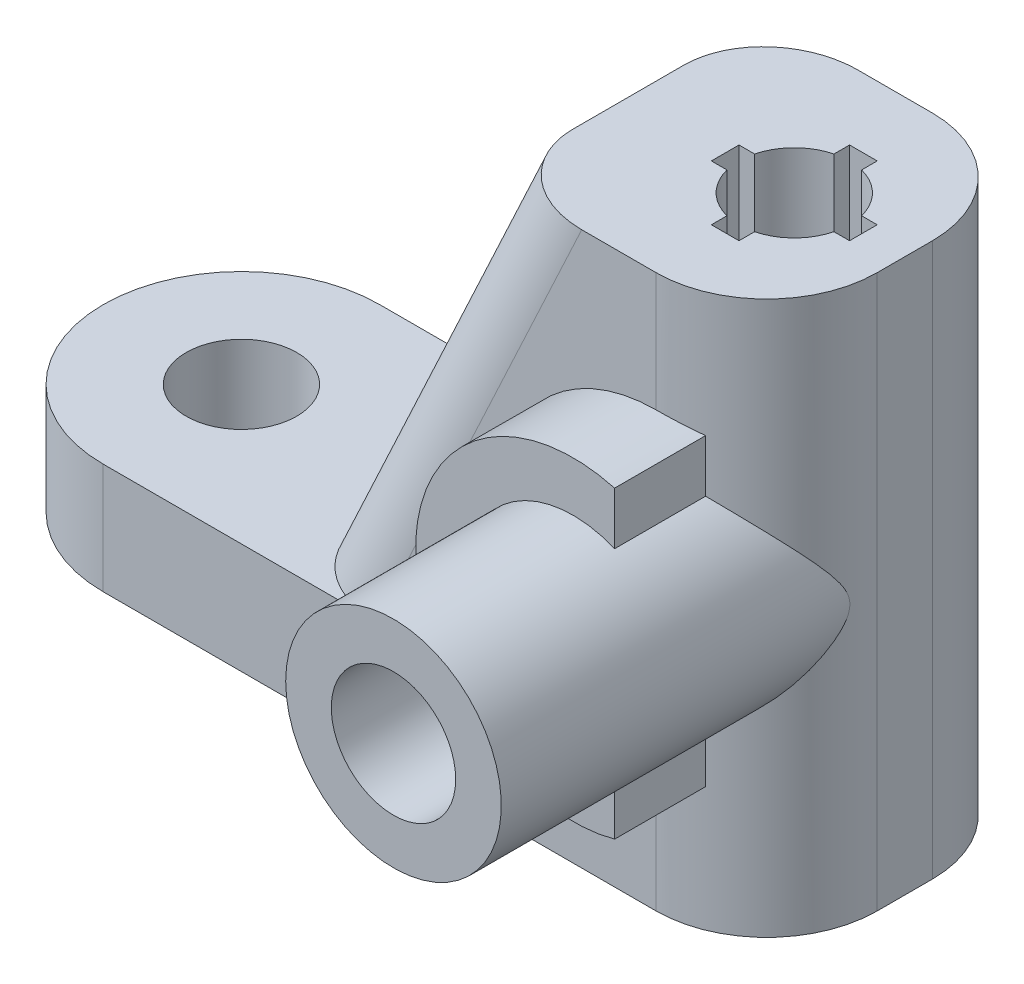
SolidWorks part; units mm, degrees
ref_plane "Front Plane" through (0, 0, 0) normal (0, 0, 1) x (1, 0, 0)
ref_plane "Top Plane" through (0, 0, 0) normal (0, 1, 0) x (1, 0, 0)
ref_plane "Right Plane" through (0, 0, 0) normal (1, 0, 0) x (0, 0, -1)
sketch "Sketch1" plane through (0, 0, 0) normal (0, 0, 1) x (1, 0, 0)
  line L0 (15, 0) -> (-15, 0) construction
  line L1 (-15, 10) -> (15, 10)
  line L2 (-15, 10) -> (-15, -10)
  line L3 (-15, -10) -> (15, -10)
  line L4 (15, 10) -> (15, -10)
  line L5 (-15, 10) -> (15, -10) construction
  line L6 (-15, -10) -> (15, 10) construction
  circle A0 centre (0, 0) radius 4 construction
  circle A1 centre (6, 0) radius 4 construction
  point P0 (0, 0)
  dimension "D3" = 8
  dimension "D4" = 8
  dimension "D5" = 6
  dimension "D1" = 20
  dimension "D2" = 30
extrude "Boss-Extrude1" add sketch "Sketch1" along normal blind 10
sketch "Sketch3" plane through (0, 10, 0) normal (0, 1, 0) x (1, 0, 0)
  line L0 (-15, -5) -> (15, -5) construction
  line L1 (-15, -10) -> (-15, 0) construction
  line L2 (15, -10) -> (15, 0) construction
  circle A0 centre (11, -5) radius 2
  dimension "D1" = 4
  dimension "D2" = 4
extrude "Cut-Extrude1" cut sketch "Sketch3" against normal through all
sketch "Sketch4" plane through (0, -10, 0) normal (0, -1, 0) x (1, 0, 0)
  line L0 (-15, 5) -> (15, 5) construction
  line L1 (-15, 10) -> (-15, 0) construction
  line L2 (15, 10) -> (15, 0) construction
  circle A0 centre (-9, 5) radius 2
  circle A2 centre (11, 5) radius 2 construction
  dimension "D1" = 4
  dimension "D2" = 20
extrude "Cut-Extrude2" cut sketch "Sketch4" against normal through all
fillet "Fillet1" radius 4 2 edges at (15, 0, 10) (15, 0, 0)
sketch "Sketch5" plane through (0, 0, 10) normal (0, 0, 1) x (1, 0, 0)
  line L0 (11, -10) -> (11, 10) construction
  circle A0 centre (11, 0) radius 3.9
  dimension "D1" = 7.8
extrude "Boss-Extrude2" add sketch "Sketch5" along normal offset from surface 0.5 and the other way up to surface other way up to face at (13.4142, 0, 8.4142)
sketch "Sketch6" plane through (0, 0, 10) normal (0, 0, 1) x (1, 0, 0)
  line L0 (-15, -6) -> (-2.4609, -6)
  line L2 (-2.4609, -6) -> (5, 10)
  line L3 (11, 10) -> (-15, 10) construction
  line L4 (5, 10) -> (-15, 10)
  line L5 (-15, 10) -> (-15, -6)
  line L6 (15, 10) -> (15, -10) construction
  line L7 (-15, -10) -> (11, -10) construction
  line L8 (-15, 10) -> (-15, -10) construction
  dimension "D1" = 10
  dimension "D2" = 4
  dimension "D3" = 115
extrude "Cut-Extrude3" cut sketch "Sketch6" against normal through all
fillet "Fillet3" radius 3 2 edges at (1.2695, 2, 10) (1.2695, 2, 0)
sketch "Sketch7" plane through (0, 0, 10) normal (0, 0, 1) x (1, 0, 0)
  line L0 (12.5, 5.4991) -> (12.5, -5.4991)
  line L1 (11, 3.9) -> (11, 10) construction
  arc A0 (12.5, 5.4991) -> (12.5, -5.4991) centre (11, 0) ccw
  circle A1 centre (11, 0) radius 5.7 construction
  arc A2 (12.5, -5.4991) -> (12.5, 5.4991) centre (11, 0) ccw construction
  dimension "D1" = 1.5
extrude "Boss-Extrude3" add sketch "Sketch7" along normal up to surface (3 mm away) and the other way up to surface
sketch "Sketch8" plane through (0, 0, 19.5) normal (0, 0, 1) x (1, 0, 0)
  circle A0 centre (11, 0) radius 2.25
  dimension "D1" = 4.5
extrude "Cut-Extrude4" cut sketch "Sketch8" against normal blind 8
sketch "Sketch9" plane through (0, -10, 0) normal (0, -1, 0) x (1, 0, 0)
  line L0 (-9, 10) -> (-15, 10)
  line L1 (-15, 10) -> (-15, 0)
  line L2 (-15, 0) -> (-9, 0)
  arc A0 (-9, 10) -> (-9, 0) centre (-9, 5) ccw
  arc A1 (-9, 0) -> (-9, 10) centre (-9, 5) ccw construction
  dimension "D1" = 10
extrude "Cut-Extrude5" cut sketch "Sketch9" against normal through all
sketch "Sketch10" plane through (0, 10, 0) normal (0, 1, 0) x (1, 0, 0)
  line L0 (11, -5) -> (9, -5) construction
  line L1 (9.5, -4.5) -> (9.5, -5) construction
  line L2 (8.5, -4.5) -> (9.0635, -4.5)
  line L3 (8.5, -4.5) -> (8.5, -5.5)
  line L4 (8.5, -5.5) -> (9.0635, -5.5)
  line L5 (9.5, -5) -> (9.5, -5.5) construction
  line L6 (8.5, -4.5) -> (9.5, -5.5) construction
  line L7 (8.5, -5.5) -> (9.5, -4.5) construction
  line L8 (9.0635, -4.5) -> (9.5, -4.5) construction
  line L9 (9.0635, -5.5) -> (9.5, -5.5) construction
  line L10 (10.5, -2.5) -> (10.5, -3.0635)
  line L11 (11.5, -2.5) -> (10.5, -2.5)
  line L12 (11.5, -2.5) -> (11.5, -3.0635)
  line L13 (13.5, -4.5) -> (12.9365, -4.5)
  line L14 (13.5, -5.5) -> (13.5, -4.5)
  line L15 (13.5, -5.5) -> (12.9365, -5.5)
  line L16 (11.5, -7.5) -> (11.5, -6.9365)
  line L17 (10.5, -7.5) -> (11.5, -7.5)
  line L18 (10.5, -7.5) -> (10.5, -6.9365)
  circle A0 centre (11, -5) radius 2 construction
  arc A1 (9.0635, -5.5) -> (9.0635, -4.5) centre (11, -5) ccw construction
  arc A2 (9, -5) -> (9.0635, -5.5) centre (11, -5) ccw
  arc A3 (9.0635, -4.5) -> (9, -5) centre (11, -5) ccw
  arc A4 (11, -3) -> (10.5, -3.0635) centre (11, -5) ccw
  arc A5 (11.5, -3.0635) -> (11, -3) centre (11, -5) ccw
  arc A6 (13, -5) -> (12.9365, -4.5) centre (11, -5) ccw
  arc A7 (12.9365, -5.5) -> (13, -5) centre (11, -5) ccw
  arc A8 (11, -7) -> (11.5, -6.9365) centre (11, -5) ccw
  arc A9 (10.5, -6.9365) -> (11, -7) centre (11, -5) ccw
  point P28 (11, -5)
  dimension "D1" = 1
  dimension "D2" = 1
  dimension "D3" = 4
extrude "Cut-Extrude6" cut sketch "Sketch10" against normal through all
mirror "Mirror1" [suppressed]
delete or keep bodies "Body-Delete/Keep 1" [suppressed] type delete bodies bodies 110
